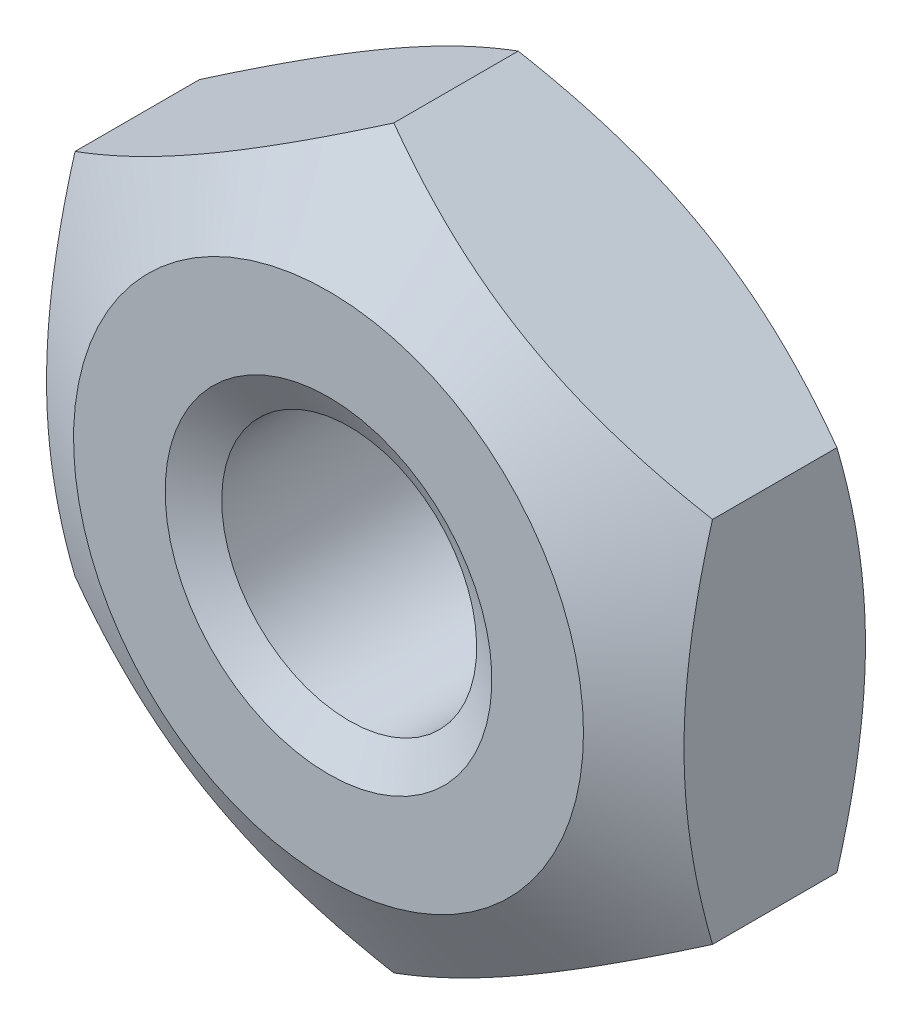
SolidWorks part; units mm, degrees
ref_plane "Front Plane" through (0, 0, 0) normal (0, 0, 1) x (1, 0, 0)
ref_plane "Top Plane" through (0, 0, 0) normal (0, 1, 0) x (1, 0, 0)
ref_plane "Right Plane" through (0, 0, 0) normal (1, 0, 0) x (0, 0, -1)
sketch "Sketch1" plane through (0, 0, 0) normal (0, 0, 1) x (1, 0, 0)
  line L0 (0, 0) -> (0, 2.3094) construction
  line L1 (0, 2.3094) -> (-2, 1.1547)
  line L2 (-2, 1.1547) -> (-2, -1.1547)
  line L3 (-2, -1.1547) -> (0, -2.3094)
  line L4 (0, -2.3094) -> (2, -1.1547)
  line L5 (2, -1.1547) -> (2, 1.1547)
  line L6 (2, 1.1547) -> (0, 2.3094)
  circle A0 centre (0, 0) radius 2 construction
  dimension "S DIM" = 4
extrude "Boss-Extrude1" add sketch "Sketch1" against normal blind 1.6
sketch "Sketch4" plane through (0, 0, 0) normal (1, 0, 0) x (0, 0, -1)
  line L0 (1.6, 2.3094) -> (1.1904, 2.3094)
  line L1 (1.6, 2.3094) -> (0, 2.3094) construction
  line L2 (1.1904, 2.3094) -> (1.6, 1.6)
  line L4 (1.6, 1.6) -> (1.6, 2.3094)
  line L5 (0, 0) -> (3.2979, 0) construction
  line L6 (0, 2.3094) -> (0.4096, 2.3094)
  line L7 (0.4096, 2.3094) -> (0, 1.6)
  line L9 (0, 1.6) -> (0, 2.3094)
  dimension "SAME S 1" = 3.2
  dimension "D2" = 30
  dimension "SAME S 2" = 3.2
  dimension "D4" = 30
revolve "Cut-Revolve1" cut sketch "Sketch4" angle 360 about L5
sketch "Sketch5" plane through (0, 0, 0) normal (1, 0, 0) x (0, 0, -1)
  line L0 (0, 0) -> (1.6, 0) construction
  line L1 (0, 0) -> (0, 1.025)
  line L2 (0, 1.6) -> (0, -1.6) construction
  line L3 (0, 1.025) -> (0.1299, 0.8)
  line L4 (0.1299, 0.8) -> (1.4701, 0.8)
  line L5 (1.4701, 0.8) -> (1.6, 1.025)
  line L6 (1.6, 1.025) -> (1.6, 0)
  line L8 (1.6, -1.6) -> (1.6, 1.6) construction
  line L9 (1.6, 0) -> (0, 0)
  dimension "D1" = 60
  dimension "D2" = 60
  dimension "Hole2" = 2.05
  dimension "Hole1" = 1.6
revolve "Cut-Revolve2" cut sketch "Sketch5" angle 360 about L0
cosmetic thread "Cosmetic Thread1" parameters "D2"=2
